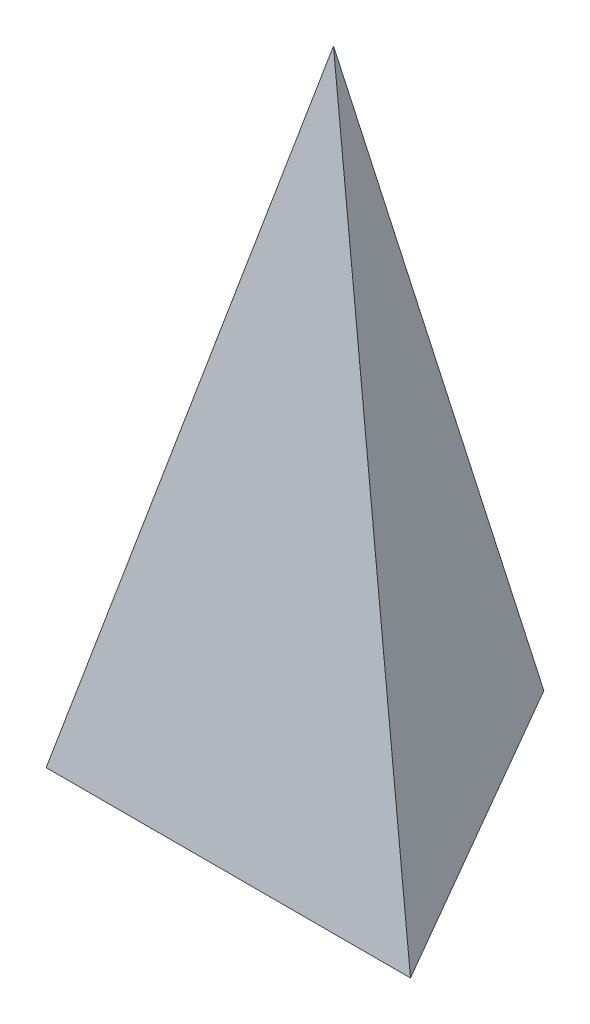
SolidWorks part; units mm, degrees
material "Pine"
ref_plane "Front Plane" through (0, 0, 0) normal (0, 0, 1) x (1, 0, 0)
ref_plane "Top Plane" through (0, 0, 0) normal (0, 1, 0) x (1, 0, 0)
ref_plane "Right Plane" through (0, 0, 0) normal (1, 0, 0) x (0, 0, -1)
sketch "Sketch1" plane through (0, 0, 0) normal (0, 1, 0) x (1, 0, 0)
  line L1 (0, 27.7707) -> (-24.0501, -13.8853)
  line L2 (-24.0501, -13.8853) -> (24.0501, -13.8853)
  line L3 (24.0501, -13.8853) -> (0, 27.7707)
  circle A0 centre (0, 0) radius 13.8853 construction
  dimension "D1" = 41.656
  dimension "D2" = 48.1002
ref_plane "Plane2" through (0, 87.6001, 0) normal (0, 1, 0) x (1, 0, 0)
sketch "Sketch2" plane through (0, 87.6001, 0) normal (0, 1, 0) x (1, 0, 0)
  point P0 (0, 0)
loft "Loft1" add profiles "Sketch2", "Sketch1"
